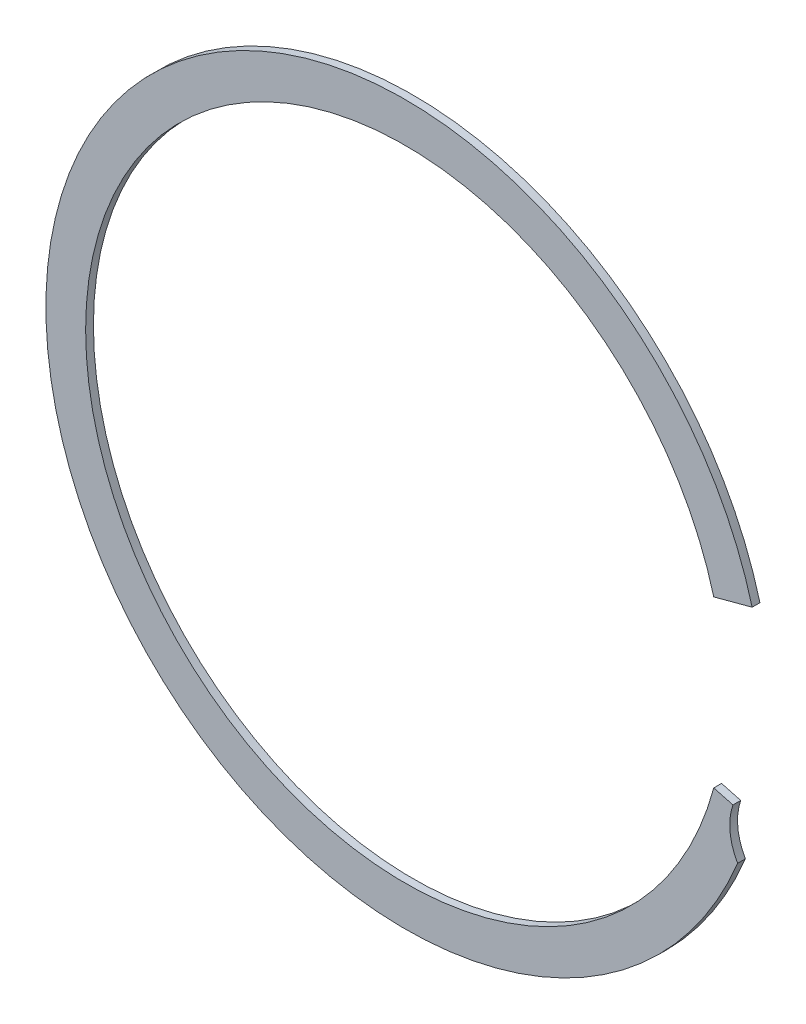
SolidWorks part; units mm, degrees
ref_plane "Front" through (0, 0, 0) normal (0, 0, 1) x (1, 0, 0)
ref_plane "Top" through (0, 0, 0) normal (0, 1, 0) x (1, 0, 0)
ref_plane "Right" through (0, 0, 0) normal (1, 0, 0) x (0, 0, -1)
sketch "Layout" plane through (0, 0, 0) normal (0, 0, 1) x (1, 0, 0)
  line L0 (-36.2839, 0) -> (36.2839, 0) construction
  line L1 (31.1711, -8.3523) -> (0, 0) construction
  line L2 (31.1711, 8.3523) -> (33.1093, 8.8716) construction
  line L3 (0, 0) -> (0, 9.071) construction
  line L4 (0, 9.071) -> (0, 18.142) construction
  line L5 (0, 18.142) -> (0, 27.2129) construction
  line L6 (0, 27.2129) -> (0, 36.2839) construction
  line L7 (31.1711, 8.3523) -> (0, 0) construction
  line L9 (-36.2839, 0) -> (-36.2839, 0.7874) construction
  line L10 (33.1093, 8.8716) -> (35.0476, 9.391) construction
  line L11 (31.1711, -8.3523) -> (33.1093, -8.8716) construction
  line L12 (33.1093, -8.8716) -> (35.0476, -9.391) construction
  line L13 (0, 27.2129) -> (57.0706, 27.2129) construction
  circle A0 centre (0, 0) radius 32.2707 construction
  circle A1 centre (0, 0) radius 36.2839 construction
  circle A2 centre (22.3004, 0) radius 13.9835 construction
  circle A3 centre (57.0706, 0) radius 27.2129 construction
  dimension "Ring OD" = 72.5678
  dimension "D1" = 15
sketch "Sketch2" plane through (0, 0, 0) normal (0, 0, 1) x (1, 0, 0)
  line L0 (-36.2839, 0) -> (36.2839, 0) construction
  line L1 (-36.2839, 0) -> (36.2839, 0) construction
  line L3 (31.1711, 8.3523) -> (33.1093, 8.8716) construction
  line L4 (33.1093, 8.8716) -> (35.0476, 9.391) construction
  line L5 (31.1711, -8.3523) -> (0, 0) construction
  line L6 (31.1711, -8.3523) -> (0, 0) construction
  line L8 (33.1093, -8.8716) -> (35.0476, -9.391) construction
  line L9 (31.1711, 8.3523) -> (33.1093, 8.8716)
  line L10 (33.1093, 8.8716) -> (35.0476, 9.391)
  line L11 (31.1711, -8.3523) -> (33.1093, -8.8716)
  circle A0 centre (0, 0) radius 36.2839 construction
  circle A3 centre (0, 0) radius 32.2707 construction
  circle A4 centre (57.0706, 0) radius 27.2129 construction
  arc A5 (35.0476, 9.391) -> (33.5815, -13.7407) centre (0, 0) ccw
  arc A6 (31.1711, 8.3523) -> (31.1711, -8.3523) centre (0, 0) ccw
  arc A7 (33.1093, -8.8716) -> (33.5815, -13.7407) centre (38.6171, -10.7949) ccw
extrude "Boss-Extrude1" add sketch "Sketch2" along normal blind 0.7874
sketch "Sketch3" plane through (0, 0, 0) normal (0, 0, 1) x (1, 0, 0)
  line L0 (0, 0) -> (35.0476, 0) construction
  line L1 (22.8188, -22.8188) -> (25.6566, -25.6566) construction
  arc A0 (31.1711, 8.3523) -> (31.1711, -8.3523) centre (0, 0) ccw construction
  arc A1 (35.0476, 9.391) -> (33.5815, -13.7407) centre (0, 0) ccw construction
  dimension "D1" = 45
sketch "Sketch4" [suppressed] plane through (0, 0, 0) normal (0, 0, 1) x (1, 0, 0)
  circle A0 centre (0, 0) radius 7.5311 construction
  arc A1 (7.2745, 1.9492) -> (6.8579, -3.1124) centre (0, 0) ccw construction
equation "\"D1@Boss-Extrude1\"=\"thickness@Layout\""
